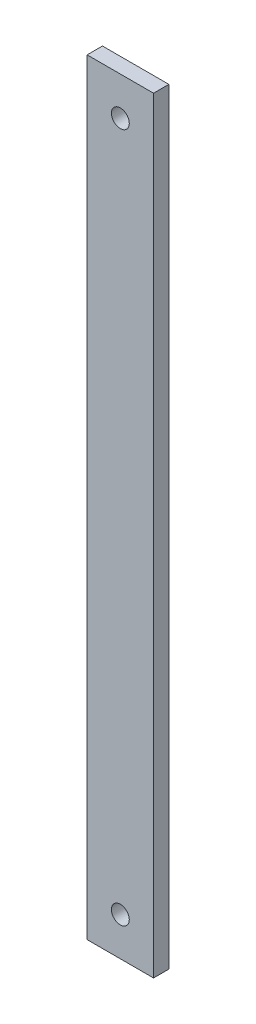
SolidWorks part; units mm, degrees
material "PMMA"
ref_plane "Płaszczyzna przednia" through (0, 0, 0) normal (0, 0, 1) x (1, 0, 0)
ref_plane "Płaszczyzna górna" through (0, 0, 0) normal (0, 1, 0) x (1, 0, 0)
ref_plane "Płaszczyzna prawa" through (0, 0, 0) normal (1, 0, 0) x (0, 0, -1)
sketch "Szkic1" plane through (0, 0, 0) normal (0, 0, 1) x (1, 0, 0)
  line L0 (0, -67.5) -> (0, -75) construction
  line L1 (-6.5, -75) -> (6.5, -75)
  line L2 (-6.5, -75) -> (-6.5, 75)
  line L3 (-6.5, 75) -> (6.5, 75)
  line L4 (6.5, -75) -> (6.5, 75)
  line L5 (0, 75) -> (0, -75) construction
  line L6 (-6.5, 0) -> (6.5, 0) construction
  line L7 (0, 75) -> (0, 67.5) construction
  circle A0 centre (0, 67.5) radius 1.75
  circle A1 centre (0, -67.5) radius 1.75
  point P0 (0, 0)
  dimension "D3" = 3.5
  dimension "D1" = 135
  dimension "D2" = 13
  dimension "D4" = 150
extrude "Dodanie-wyciągnięcie1" add sketch "Szkic1" along normal blind 3
equation "\"D4@Szkic1\"=\"D1@Szkic1\"+15"
